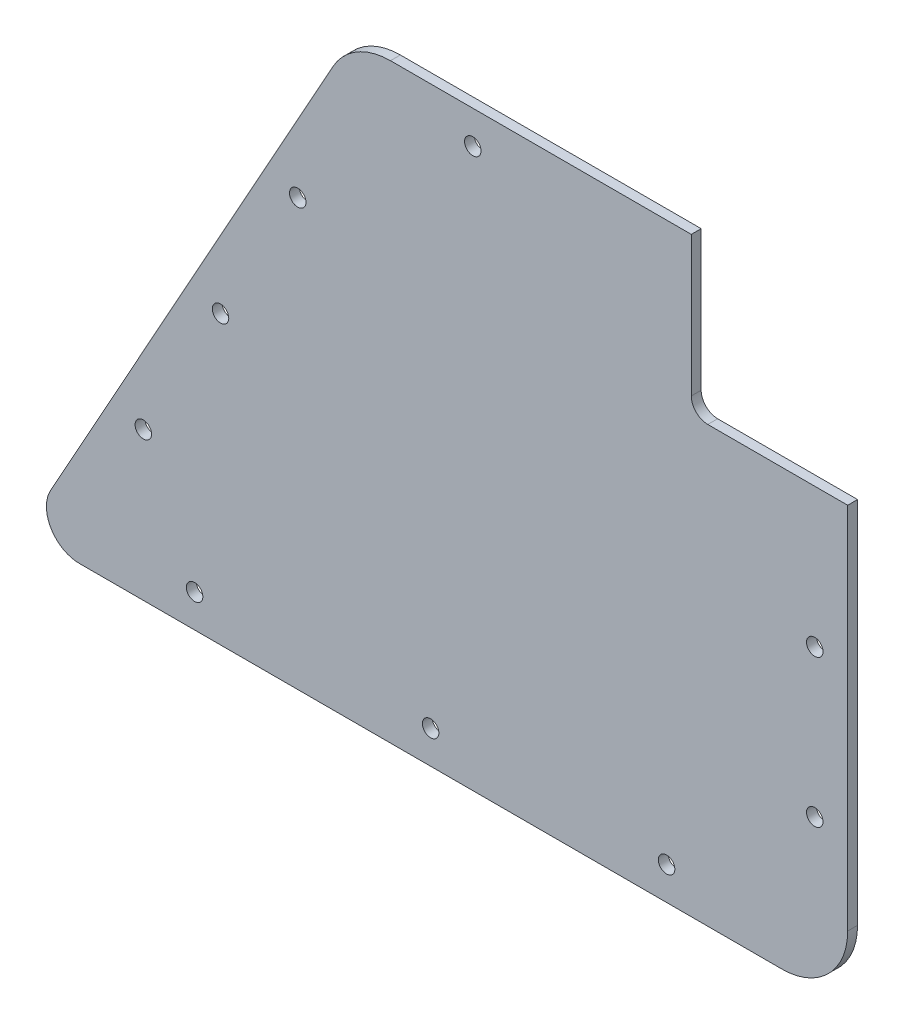
SolidWorks part; units mm, degrees
ref_plane "Front Plane" through (0, 0, 0) normal (0, 0, 1) x (1, 0, 0)
ref_plane "Top Plane" through (0, 0, 0) normal (0, 1, 0) x (1, 0, 0)
ref_plane "Right Plane" through (0, 0, 0) normal (1, 0, 0) x (0, 0, -1)
sketch "Sketch1" plane through (0, 0, 0) normal (0, 0, 1) x (1, 0, 0)
  line L0 (-1232.9818, 0) -> (48767.0182, 0) construction
  line L1 (-59.4361, 179.5) -> (59.4361, 179.5)
  line L2 (-76.9192, 169.2129) -> (-162.6728, 14.8564)
  line L3 (-153.9312, 0) -> (59.4361, 0)
  line L4 (79.4361, 20) -> (79.4361, 159.5)
  arc A0 (-153.9312, 0) -> (-162.6728, 14.8564) centre (-153.9312, 10) cw
  arc A1 (59.4361, 0) -> (79.4361, 20) centre (59.4361, 20) ccw
  arc A2 (79.4361, 159.5) -> (59.4361, 179.5) centre (59.4361, 159.5) ccw
  arc A3 (-76.9192, 169.2129) -> (-59.4361, 179.5) centre (-59.4361, 159.5) cw
  point P3 (0, 179.5)
  dimension "D1" = 10
  dimension "D2" = 20
  dimension "D3" = 20
  dimension "D4" = 20
  dimension "D5" = 179.5
  dimension "D6" = 176.5774
  dimension "D7" = 213.3673
extrude "Boss-Extrude1" add sketch "Sketch1" along normal blind 3
sketch "Sketch2" plane through (0, 0, 3) normal (0, 0, 1) x (1, 0, 0)
  line L0 (-34.4361, 184.5) -> (-34.4361, 169.5) construction
  line L1 (59.4361, 179.5) -> (-59.4361, 179.5) construction
  line L2 (79.4361, 20) -> (79.4361, 159.5) construction
  line L3 (-34.4361, 169.5) -> (34.4339, 169.5) construction
  line L4 (84.4361, 134.5) -> (69.4361, 134.5) construction
  line L5 (69.4361, 134.5) -> (69.4361, 89.75) construction
  line L6 (24.4361, -5) -> (24.4361, 10) construction
  line L7 (-153.9312, 0) -> (59.4361, 0) construction
  line L8 (24.4361, 10) -> (-47.2439, 10) construction
  line L9 (-147.6179, 52.2509) -> (-134.5055, 44.9663) construction
  line L11 (-76.9192, 169.2129) -> (-162.6728, 14.8564) construction
  line L12 (-134.5055, 44.9663) -> (-87.6021, 129.3924) construction
  circle A0 centre (-34.4361, 169.5) radius 2.5
  circle A1 centre (34.4339, 169.5) radius 2.5
  circle A2 centre (69.4361, 134.5) radius 2.5
  circle A3 centre (69.4361, 89.75) radius 2.5
  circle A4 centre (69.4361, 45) radius 2.5
  circle A5 centre (24.4361, 10) radius 2.5
  circle A6 centre (-47.2439, 10) radius 2.5
  circle A7 centre (-118.9239, 10) radius 2.5
  circle A8 centre (-134.5055, 44.9663) radius 2.5
  circle A9 centre (-87.6021, 129.3924) radius 2.5
  circle A10 centre (-111.0538, 87.1793) radius 2.5
  point P38 (0, 0)
  dimension "D1" = 5
  dimension "D2" = 15
  dimension "D3" = 5
  dimension "D4" = 113.8722
  dimension "D5" = 68.87
  dimension "D6" = 5
  dimension "D7" = 15
  dimension "D8" = 45
  dimension "D10" = 44.75
  dimension "D11" = 5
  dimension "D12" = 15
  dimension "D13" = 55
  dimension "D15" = 71.68
  dimension "D16" = 5
  dimension "D17" = 15
  dimension "D18" = 44.9663
  dimension "D19" = 96.58
  dimension "D9" = 3
  dimension "D14" = 3
extrude "Cut-Extrude1" cut sketch "Sketch2" against normal up to next
sketch "Sketch3" plane through (0, 0, 3) normal (0, 0, 1) x (1, 0, 0)
  line L0 (31.9339, 179.5) -> (31.9339, 137)
  line L1 (59.4361, 179.5) -> (-59.4361, 179.5) construction
  line L2 (79.4361, 132) -> (36.9339, 132)
  line L3 (79.4361, 20) -> (79.4361, 159.5) construction
  line L4 (79.4361, 132) -> (79.4361, 159.5)
  line L5 (59.4361, 179.5) -> (31.9339, 179.5)
  circle A0 centre (69.4361, 134.5) radius 2.5 construction
  circle A1 centre (34.4339, 169.5) radius 2.5 construction
  arc A2 (79.4361, 159.5) -> (59.4361, 179.5) centre (59.4361, 159.5) ccw construction
  arc A3 (79.4361, 159.5) -> (59.4361, 179.5) centre (59.4361, 159.5) ccw
  arc A4 (31.9339, 137) -> (36.9339, 132) centre (36.9339, 137) ccw
  dimension "D1" = 5
extrude "Cut-Extrude2" cut sketch "Sketch3" against normal through all
